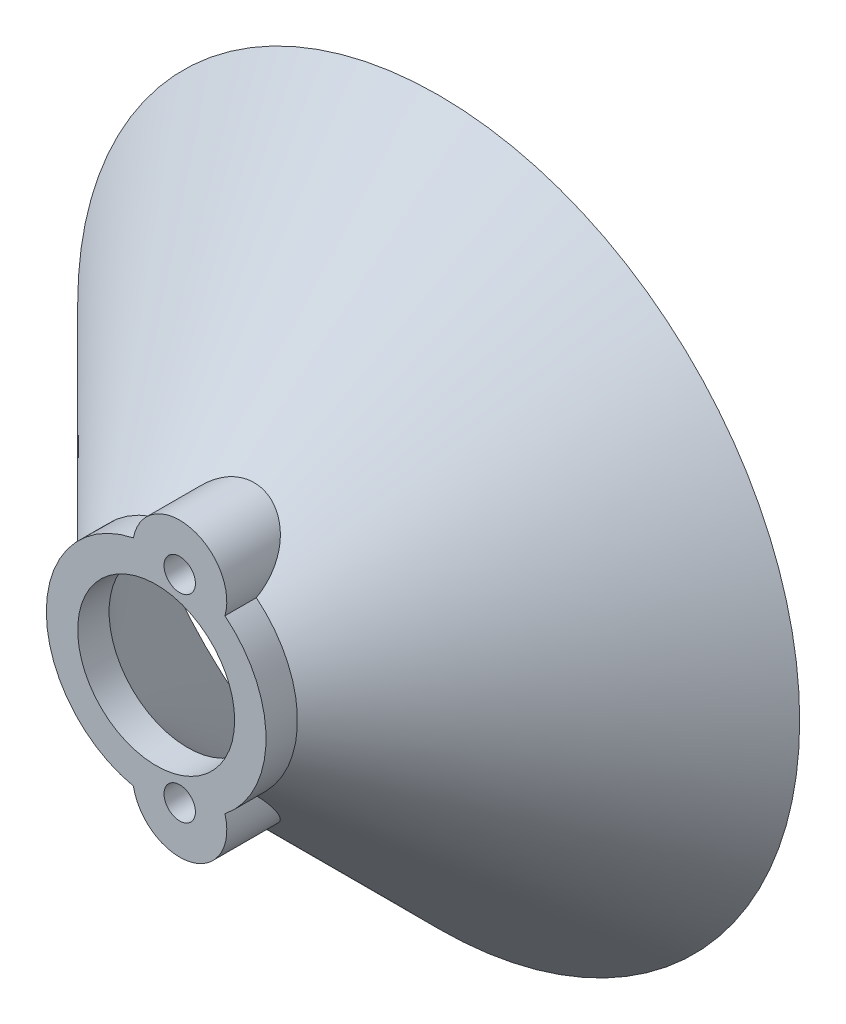
SolidWorks part; units mm, degrees
ref_plane "Спереди" through (0, 0, 0) normal (0, 0, 1) x (1, 0, 0)
ref_plane "Сверху" through (0, 0, 0) normal (0, 1, 0) x (1, 0, 0)
ref_plane "Справа" through (0, 0, 0) normal (1, 0, 0) x (0, 0, -1)
other "Configuration Table"
sketch "Эскиз1" plane through (0, 0, 0) normal (0, 0, 1) x (1, 0, 0)
  line L0 (0, 0) -> (1.5, 0) construction
  line L1 (1.5, 0) -> (1.5, 6.3) construction
  line L2 (1.5, 0) -> (1.5, -6.3) construction
  circle A0 centre (0, 0) radius 5
  circle A2 centre (0, 0) radius 7
  circle A3 centre (1.5, 6.3) radius 1
  circle A4 centre (1.5, -6.3) radius 1
  circle A5 centre (1.5, 6.3) radius 3
  circle A6 centre (1.5, -6.3) radius 3
  dimension "D1" = 10
  dimension "D2" = 2
  dimension "D6" = 2
  dimension "D7" = 2
  dimension "D3" = 1.5
  dimension "D4" = 6.3
  dimension "D5" = 6.3
extrude "Бобышка-Вытянуть1" add sketch "Эскиз1" along normal blind 2 contours A6 A0 A5 A2 | A6 A2 A5 A0 | A2 A5 A0 A3 | A2 A6 A0 A4 | A2 A6 A4 | A2 A5 A3
sketch "Эскиз2" plane through (0, 0, 0) normal (0, 0, -1) x (-1, 0, 0)
  circle A2 centre (0, 0) radius 7
extrude "Бобышка-Вытянуть2" add sketch "Эскиз2" along normal blind 16 draft 45 draft outward yes
sketch "Эскиз3" plane through (0, 0, 0) normal (0, 0, 1) x (1, 0, 0)
  circle A1 centre (0, 0) radius 5
  circle A2 centre (0, 0) radius 5
  dimension "D1" = 0
extrude "Вырез-Вытянуть1" cut sketch "Эскиз3" against normal through all draft 45 draft outward yes
sketch "Эскиз4" plane through (0, 0, 0) normal (0, 0, -1) x (-1, 0, 0)
  arc A4 (-4.3801, -5.4603) -> (-2.4681, -6.5504) centre (0, 0) ccw
  arc A5 (-4.3801, -5.4603) -> (1.4495, -6.8483) centre (-1.5, -6.3) ccw
  arc A6 (-0.7486, -6.9599) -> (1.4495, -6.8483) centre (0, 0) ccw
  arc A7 (-2.4681, -6.5504) -> (-0.7486, -6.9599) centre (-1.5, -6.3) ccw
  arc A8 (-4.3801, -5.4603) -> (-2.4681, -6.5504) centre (0, 0) ccw
  arc A9 (-4.3801, -5.4603) -> (1.4495, -6.8483) centre (-1.5, -6.3) ccw
  arc A10 (-0.7486, -6.9599) -> (1.4495, -6.8483) centre (0, 0) ccw
  arc A11 (-2.4681, -6.5504) -> (-0.7486, -6.9599) centre (-1.5, -6.3) ccw
  arc A12 (1.4495, 6.8483) -> (-0.7486, 6.9599) centre (0, 0) ccw
  arc A13 (1.4495, 6.8483) -> (-4.3801, 5.4603) centre (-1.5, 6.3) ccw
  arc A14 (-2.4681, 6.5504) -> (-4.3801, 5.4603) centre (0, 0) ccw
  arc A15 (-0.7486, 6.9599) -> (-2.4681, 6.5504) centre (-1.5, 6.3) ccw
  arc A16 (1.4495, 6.8483) -> (-0.7486, 6.9599) centre (0, 0) ccw
  arc A17 (1.4495, 6.8483) -> (-4.3801, 5.4603) centre (-1.5, 6.3) ccw
  arc A18 (-2.4681, 6.5504) -> (-4.3801, 5.4603) centre (0, 0) ccw
  arc A19 (-0.7486, 6.9599) -> (-2.4681, 6.5504) centre (-1.5, 6.3) ccw
  dimension "D1" = 0
  dimension "D2" = 0
extrude "Бобышка-Вытянуть3" add sketch "Эскиз4" along normal up to next
sketch "Эскиз5" plane through (0, 0, 0) normal (0, 0, 1) x (1, 0, 0)
  circle A14 centre (1.5, 6.3) radius 1 construction
  circle A15 centre (1.5, 6.3) radius 1
  circle A16 centre (1.5, -6.3) radius 1 construction
  circle A17 centre (1.5, -6.3) radius 1
extrude "Бобышка-Вытянуть5" add sketch "Эскиз5" against normal up to body
